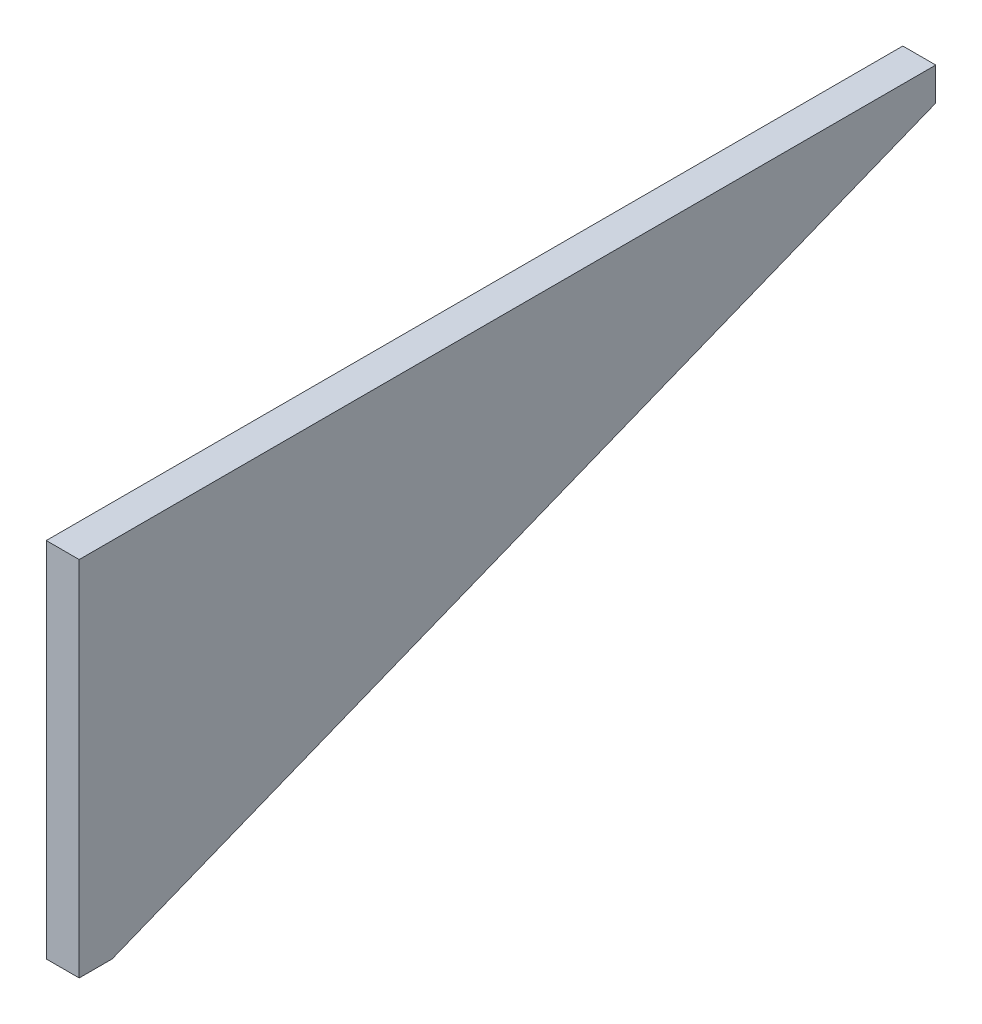
SolidWorks part; units mm, degrees
ref_plane "Front Plane" through (0, 0, 0) normal (0, 0, 1) x (1, 0, 0)
ref_plane "Top Plane" through (0, 0, 0) normal (0, 1, 0) x (1, 0, 0)
ref_plane "Right Plane" through (0, 0, 0) normal (1, 0, 0) x (0, 0, -1)
sketch "Sketch1" plane through (0, 0, 0) normal (1, 0, 0) x (0, 0, -1)
  line L0 (0, 0) -> (52, 0)
  line L1 (52, 0) -> (52, -2)
  line L2 (52, -2) -> (2, -22)
  line L3 (2, -22) -> (0, -22)
  line L4 (0, -22) -> (0, 0)
  dimension "D1" = 2
  dimension "D2" = 22
  dimension "D3" = 50
extrude "Boss-Extrude1" add sketch "Sketch1" along normal blind 2
